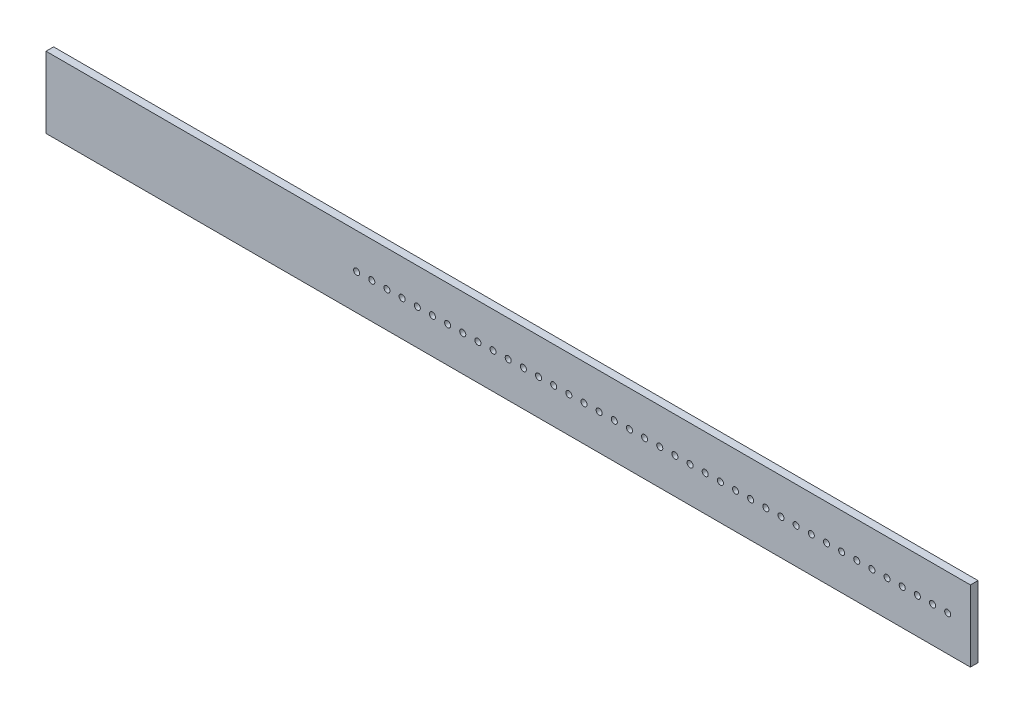
SolidWorks part; units mm, degrees
material "Q235A"
ref_plane "前视" through (0, 0, 0) normal (0, 0, 1) x (1, 0, 0)
ref_plane "上视" through (0, 0, 0) normal (0, 1, 0) x (1, 0, 0)
ref_plane "右视" through (0, 0, 0) normal (1, 0, 0) x (0, 0, -1)
sketch "草图1" plane through (0, 0, 0) normal (0, 0, 1) x (1, 0, 0)
  line L1 (610, -47) -> (-610, -47)
  line L2 (610, -47) -> (610, 47)
  line L3 (610, 47) -> (-610, 47)
  line L4 (-610, -47) -> (-610, 47)
  line L5 (610, -47) -> (-610, 47) construction
  line L6 (610, 47) -> (-610, -47) construction
  point P0 (0, 0)
  dimension "D1" = 94
  dimension "D2" = 1220
extrude "凸台-拉伸1" add sketch "草图1" along normal blind 10
hole_wizard "大小mm 暗销孔1" positions "草图3" profile "草图2" hole size "Ø8.0" standard "GB" end condition through all
sketch "草图3" plane through (0, 0, 0) normal (0, 0, -1) x (-1, 0, 0)
  line L1 (610, -47) -> (-610, -47) construction
  line L2 (-610, -47) -> (-610, 47) construction
  point P0 (-580, 0)
  dimension "D1" = 47
  dimension "D2" = 30
sketch "草图2" plane through (580, 0, 0) normal (1, 0, 0) x (0, 1, 0)
  line L0 (0, 0) -> (0, 10)
  line L1 (0, 10) -> (4, 10)
  line L2 (4, 10) -> (4, 0)
  line L5 (4, 0) -> (0, 0)
  line L11 (0, -6.35) -> (0, 107.95) construction
  dimension "通孔孔直径" = 8
  dimension "通孔孔深度" = 10
pattern_linear "阵列(线性)1" count 40 spacing 20 along (-1, 0, 0) of "大小mm 暗销孔1"
